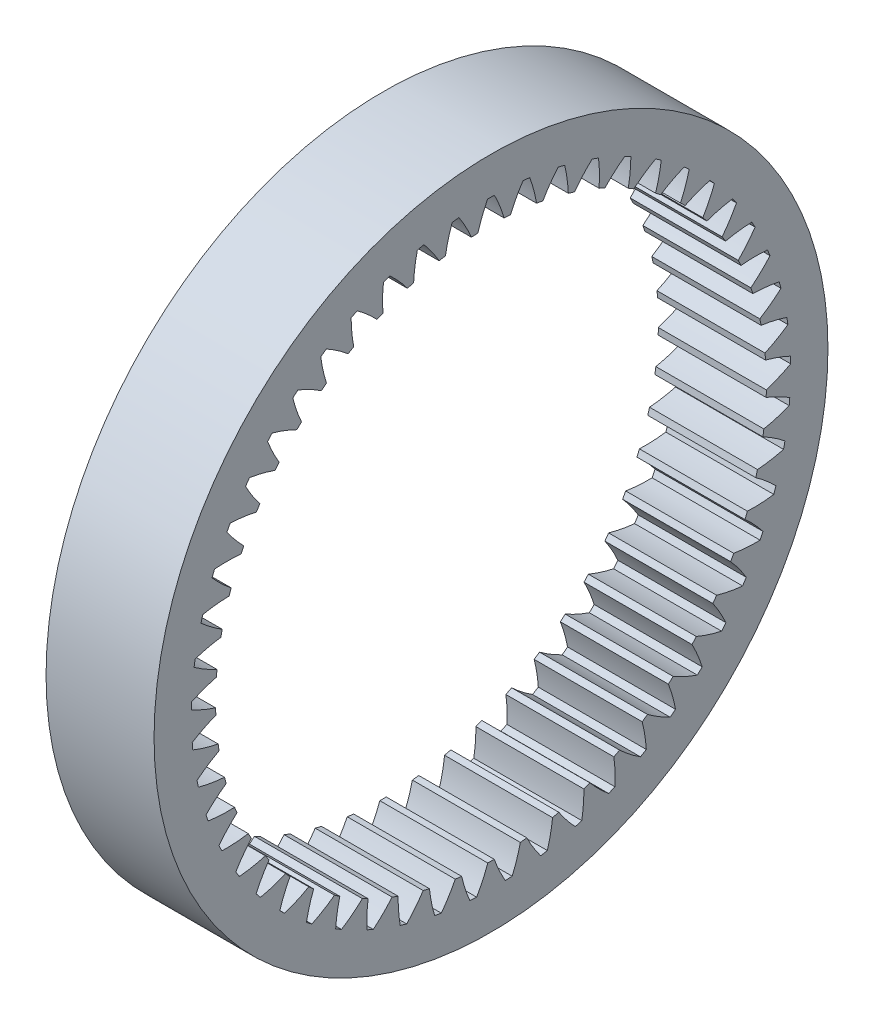
SolidWorks part; units mm, degrees
ref_plane "Plane1" through (0, 0, 0) normal (0, 0, 1) x (1, 0, 0)
ref_plane "Plane2" through (0, 0, 0) normal (0, 1, 0) x (1, 0, 0)
ref_plane "Plane3" through (0, 0, 0) normal (1, 0, 0) x (0, 0, -1)
sketch "HoldingSke" plane through (0, 0, 0) normal (0, 1, 0) x (1, 0, 0)
  line L0 (0, 0) -> (0.2407, -0.3195)
  line L1 (-15, 0) -> (100, 0) construction
  line L2 (0, 0) -> (-2.1039, 2.3779)
  line L3 (0, 0) -> (-11.863, 4.5341)
  line L4 (0, 0) -> (5.1973, 6.897)
  line L5 (0, 0) -> (-23.7986, -8.8762)
  line L6 (0, 0) -> (-10.5278, -7.1032)
  line L7 (-2.1039, 2.3779) -> (3.3635, 27.1825)
  line L8 (-76.2, 4.8779) -> (-54.61, 4.8779)
  line L9 (-71.009, 38.7566) -> (-53.1078, 45.2721)
  line L10 (-76.2, 71.12) -> (104.1128, 71.12)
  line L11 (0, 0) -> (-25, 0)
  line L12 (-76.2, 101.6) -> (-76.113, 101.6)
  line L13 (24.9733, 27.94) -> (52.9518, 28.4284)
  line L14 (24.9733, 27.94) -> (24.9743, 27.94)
  line L15 (24.9733, 27.94) -> (100.4006, 29.5858)
  circle A0 centre (0, 0) radius 78
  circle A1 centre (0, 0) radius 12.7
  circle A2 centre (0, 0) radius 12.7
  dimension "MHD" = 25.4
  dimension "Hub_dia" = 25.4
  dimension "Diameter" = 156
  dimension "Num_teeth" = 53
  dimension "Pitch" = 0.4
  dimension "Overall_len" = 25.4
  dimension "Show_teeth" = 53
  dimension "Thickness" = 12.7
  dimension "OAL" = 25.4001
  dimension "T_dim" = 21.59
  dimension "Ap" = 20
  dimension "H" = 19.05
  dimension "Pitch_radius" = 180.3128
  dimension "Width" = 25
  dimension "Backlash" = 0.087
  dimension "Addendum_fac" = 1
  dimension "Dedendum_fac" = 1.25
  dimension "Clearance_fac" = 0.25
  dimension "Dedendum_add" = 0.001
  dimension "Module" = 2.5
sketch "BasProSke" plane through (0, 0, 0) normal (0, 1, 0) x (1, 0, 0)
  line L0 (-10, 0) -> (60, 0) construction
  line L1 (0, 63.75) -> (0, 78)
  line L2 (0, 63.75) -> (25, 63.75)
  line L3 (25, 63.75) -> (25, 78)
  line L4 (25, 78) -> (0, 78)
  dimension "Diameter" = 156
  dimension "Thickness" = 25
  dimension "Inside_diameter" = 127.5
revolve "Base-Revolve" add sketch "BasProSke" angle 360 about L0
sketch "TooCutSke" plane through (0, 0, 0) normal (1, 0, 0) x (0, 0, -1)
  line L3 (2.1807, 66.2141) -> (2.1807, 53.6633) construction
  line L4 (0, 0) -> (0, 59.563) construction
  line L5 (0, 0) -> (-4.0478, 68.2075) construction
  line L6 (-28.7736, 54.4202) -> (34.4571, 58.1726) construction
  circle A0 centre (0, 0) radius 66.25 construction
  circle A1 centre (0, 0) radius 69.376 construction
  circle A2 centre (0, 0) radius 56.0292 construction
  circle A3 centre (0, 0) radius 63.7246 construction
  arc A4 (3.0389, 63.6521) -> (0.7852, 69.3716) centre (-28.7736, 54.4202) ccw
  arc A5 (3.0389, 63.6521) -> (-3.0389, 63.6521) centre (0, 0) ccw
  arc A6 (0.7852, 69.3716) -> (-0.7852, 69.3716) centre (0, 0) ccw
  arc A7 (-0.7852, 69.3716) -> (-3.0389, 63.6521) centre (28.7736, 54.4202) ccw
  dimension "Pitch_dia" = 132.5
  dimension "Base_dia" = 112.0583
  dimension "Root_dia" = 138.752
  dimension "Overcut_dia" = 127.4492
  dimension "Flank_rad" = 33.125
  dimension "Half_ang" = 3.396
  dimension "Half_CT" = 2.1807
extrude "ToothCut" cut sketch "TooCutSke" along normal through all
fillet "Breaks" [suppressed] radius 0.25
fillet "RootFillets" [suppressed] radius 0.626
pattern_circular "TeethCuts" count 53 over 360 about axis through (0, 0, 0) along (1, 0, 0) of "RootFillets", "Breaks", "ToothCut"
equation "' \"Module@HoldingSke\" = 6.35"
equation "' \"Num_teeth@HoldingSke\" = 24"
equation "' \"Ap@HoldingSke\" =  14.5"
equation "' \"Ap@HoldingSke\" = 14.5"
equation "' \"Width@HoldingSke\" = 12"
equation "' \"Diameter@HoldingSke\" = 8 * 25.4"
equation "' \"Show_teeth@HoldingSke\" = 100"
equation "' \"Backlash@HoldingSke\" = 0.009 * 25.4"
equation "' \"Addendum_fac@HoldingSke\" = 1.0"
equation "' \"Dedendum_fac@HoldingSke\" = 1.25"
equation "' \"Dedendum_add@HoldingSke\" = 0.00005 * 25.4"
equation "' \"Clearance_fac@HoldingSke\" = 0.25"
equation "\"Pitch@HoldingSke\" = 1 / \"Module@HoldingSke\" "
equation "\"Overcut_dia@TooCutSke\" = (\"Num_teeth@HoldingSke\" - 2 * \"Addendum_fac@HoldingSke\") / \"Pitch@HoldingSke\" - 0.002 * 25.4"
equation "\"Pitch_dia@TooCutSke\" = \"Num_teeth@HoldingSke\" / \"Pitch@HoldingSke\""
equation "\"Base_dia@TooCutSke\" = \"Num_teeth@HoldingSke\" / \"Pitch@HoldingSke\" * cos((\"Ap@HoldingSke\"  * 3.14159265 / 180)) * 0.90"
equation "\"Root_dia@TooCutSke\" = \"Num_teeth@HoldingSke\"  / \"Pitch@HoldingSke\" + 2 *  \"Dedendum_fac@HoldingSke\"/ \"Pitch@HoldingSke\" + \"Dedendum_add@HoldingSke\" * 2"
equation "\"Half_ang@TooCutSke\" = 180 / \"Num_teeth@HoldingSke\""
equation "\"Half_CT@TooCutSke\" = \"Num_teeth@HoldingSke\" / \"Pitch@HoldingSke\" * sin((3.14159265 / 2 / \"Num_teeth@HoldingSke\")) / 2 + 10 * \"Backlash@HoldingSke\" / 4"
equation "\"Flank_rad@TooCutSke\" = \"Num_teeth@HoldingSke\" / \"Pitch@HoldingSke\" / 4"
equation "\"Radius@RootFillets\"= \"Clearance_fac@HoldingSke\" / \"Pitch@HoldingSke\" + \"Dedendum_add@HoldingSke\""
equation "\"Break_rad@Breaks\" = 0.02 / \"Pitch@HoldingSke\" * 5"
equation "\"Num_teeth@TeethCuts\" = int( \"Show_teeth@HoldingSke\" ) + 1"
equation "\"Num_teeth@TeethCuts\" = ((sgn( \"Num_teeth@TeethCuts\" - \"Num_teeth@HoldingSke\" )-1)*( \"Num_teeth@TeethCuts\" - \"Num_teeth@HoldingSke\" ))/-2+ \"Num_teeth@HoldingSke\""
equation "\"Num_teeth@TeethCuts\" = ((sgn( \"Num_teeth@TeethCuts\" - 2.0)+1)*( \"Num_teeth@TeethCuts\" - 2.0))/2 +2.0"
equation "\"Angle@TeethCuts\" = 360.0 / \"Num_teeth@HoldingSke\""
equation "\"Diameter@BasProSke\" = \"Num_teeth@HoldingSke\"  / \"Pitch@HoldingSke\" + 2 *  \"Dedendum_fac@HoldingSke\"/ \"Pitch@HoldingSke\" + \"Dedendum_add@HoldingSke\" * 2 + 0.002 * 25.4"
equation "\"Diameter@BasProSke\" = ((sgn( \"Diameter@BasProSke\"  - \"Diameter@HoldingSke\" )+1)*( \"Diameter@BasProSke\"  - \"Diameter@HoldingSke\" ))/2 + \"Diameter@HoldingSke\""
equation "\"Inside_diameter@BasProSke\" =  (\"Num_teeth@HoldingSke\" - 2 * \"Addendum_fac@HoldingSke\") / \"Pitch@HoldingSke\" "
equation "\"Thickness@BasProSke\"  = \"Width@HoldingSke\""
